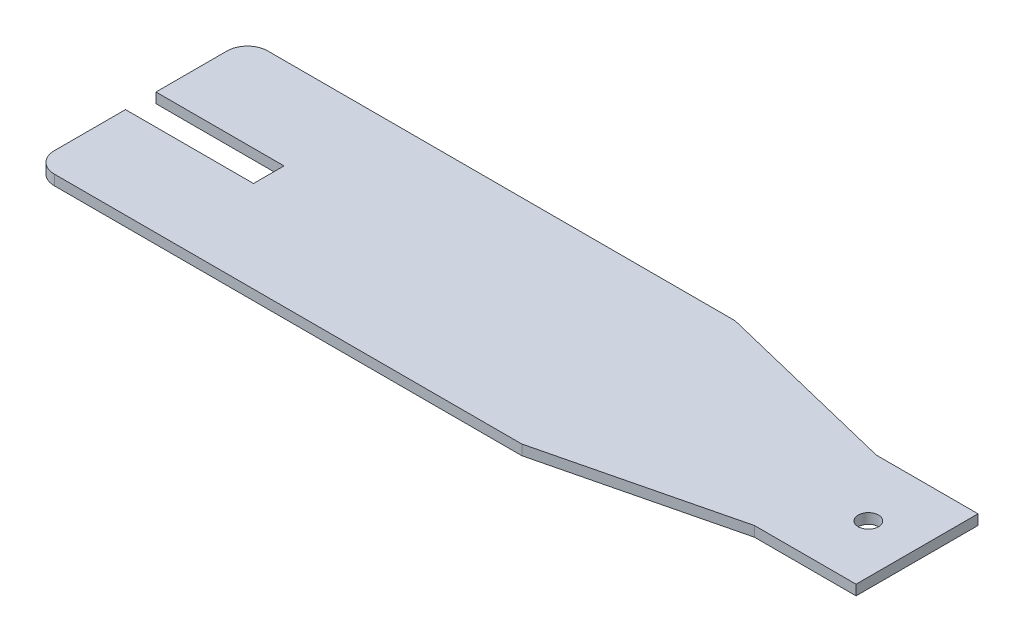
SolidWorks part; units mm, degrees
ref_plane "Front Plane" through (0, 0, 0) normal (0, 0, 1) x (1, 0, 0)
ref_plane "Top Plane" through (0, 0, 0) normal (0, 1, 0) x (1, 0, 0)
ref_plane "Right Plane" through (0, 0, 0) normal (1, 0, 0) x (0, 0, -1)
sketch "Sketch1" plane through (0, 0, 0) normal (0, 1, 0) x (1, 0, 0)
  line L0 (42.7657, -9.6045) -> (226.0642, -9.6045) construction
  line L1 (49, -62.1045) -> (-181, -62.1045)
  line L2 (191, -39.6045) -> (191, 20.3955)
  line L3 (49, 42.8955) -> (-181, 42.8955)
  line L4 (-191, -52.1045) -> (-191, -17.1045)
  line L5 (276.5313, -62.1045) -> (-191, 42.8955) construction
  line L6 (190.5245, 61.9499) -> (-191, -62.1045) construction
  line L7 (191, 20.3955) -> (141, 20.3955)
  line L8 (191, -39.6045) -> (141, -39.6045)
  line L9 (141, 20.3955) -> (49, 42.8955)
  line L10 (141, -39.6045) -> (49, -62.1045)
  line L11 (-191, -2.1045) -> (-128, -2.1045)
  line L12 (-191, -17.1045) -> (-128, -17.1045)
  line L13 (-128, -2.1045) -> (-128, -17.1045)
  line L14 (-191, -2.1045) -> (-191, 32.8955)
  arc A0 (-181, -62.1045) -> (-191, -52.1045) centre (-181, -52.1045) cw
  arc A1 (-181, 42.8955) -> (-191, 32.8955) centre (-181, 32.8955) ccw
  circle A2 centre (167.0537, -9.6045) radius 5
  point P0 (0, 0)
  dimension "D3" = 10
  dimension "D9" = 10
  dimension "D2" = 105
  dimension "D4" = 60
  dimension "D5" = 50
  dimension "D6" = 240
  dimension "D7" = 63
  dimension "D8" = 15
  dimension "D10" = 23.9463
  dimension "D11" = 382
extrude "Boss-Extrude1" add sketch "Sketch1" along normal blind 5
